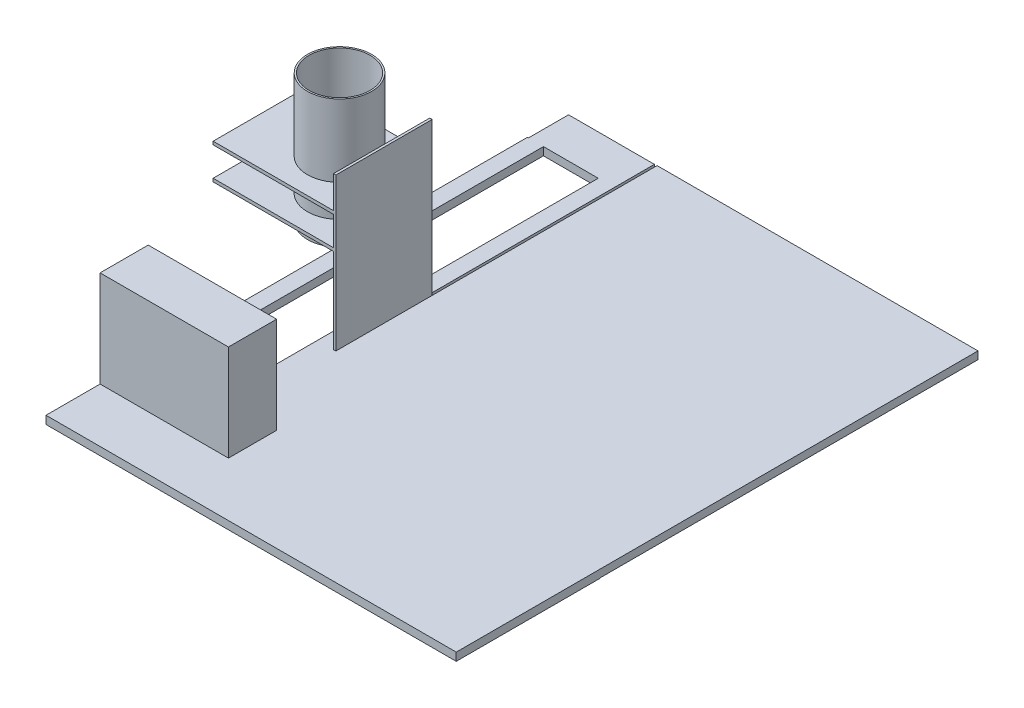
SolidWorks part; units mm, degrees
ref_plane "Front Plane" through (0, 0, 0) normal (0, 0, 1) x (1, 0, 0)
ref_plane "Top Plane" through (0, 0, 0) normal (0, 1, 0) x (1, 0, 0)
ref_plane "Right Plane" through (0, 0, 0) normal (1, 0, 0) x (0, 0, -1)
sketch "Sketch1" plane through (0, 0, 0) normal (0, 1, 0) x (1, 0, 0)
  line L1 (-61.8196, -100.3287) -> (-41.8196, -100.3287)
  line L2 (-61.8196, -100.3287) -> (-61.8196, 249.6713)
  line L3 (-61.8196, 249.6713) -> (-41.8196, 249.6713)
  line L4 (-41.8196, -100.3287) -> (-41.8196, 249.6713)
  line L5 (46.5104, -100.3287) -> (26.5104, -100.3287)
  line L6 (46.5104, -100.3287) -> (46.5104, 249.6713)
  line L7 (46.5104, 249.6713) -> (26.5104, 249.6713)
  line L8 (26.5104, -100.3287) -> (26.5104, 249.6713)
  dimension "D1" = 20
  dimension "D2" = 20
  dimension "D3" = 350
  dimension "D4" = 350
  dimension "D5" = 68.33
extrude "Boss-Extrude1" add sketch "Sketch1" along normal blind 10
sketch "Sketch2" plane through (0, 0, 0) normal (0, -1, 0) x (-1, 0, 0)
  line L1 (-46.5104, 249.6713) -> (60.5056, 249.6713)
  line L2 (-46.5104, 249.6713) -> (-46.5104, 299.6713)
  line L3 (-46.5104, 299.6713) -> (60.5056, 299.6713)
  line L4 (60.5056, 249.6713) -> (60.5056, 299.6713)
  dimension "D1" = 50
extrude "Boss-Extrude2" add sketch "Sketch2" along normal blind 0.001 and the other way blind 10
sketch "Sketch3" plane through (46.5104, 0, 0) normal (1, 0, 0) x (0, 0, -1)
  line L1 (-100.3287, 0) -> (19.6713, 0)
  line L2 (-100.3287, 0) -> (-100.3287, 200)
  line L3 (-100.3287, 200) -> (19.6713, 200)
  line L4 (19.6713, 0) -> (19.6713, 200)
  dimension "D1" = 120
  dimension "D2" = 200
extrude "Boss-Extrude3" add sketch "Sketch3" along normal blind 3
sketch "Sketch4" plane through (46.5104, 0, 0) normal (-1, 0, 0) x (0, 0, 1)
  line L0 (-19.6713, 10) -> (-19.6713, 200) construction
  line L1 (-19.6713, 160) -> (100.3287, 160)
  line L2 (-19.6713, 160) -> (-19.6713, 156)
  line L3 (-19.6713, 156) -> (100.3287, 156)
  line L4 (100.3287, 160) -> (100.3287, 156)
  line L5 (100.3287, 200) -> (100.3287, 10) construction
  line L6 (-19.6713, 200) -> (100.3287, 200) construction
  line L7 (100.3287, 120) -> (-19.6713, 120)
  line L8 (100.3287, 120) -> (100.3287, 116)
  line L9 (100.3287, 116) -> (-19.6713, 116)
  line L10 (-19.6713, 120) -> (-19.6713, 116)
  dimension "D1" = 40
  dimension "D2" = 80
  dimension "D3" = 4
  dimension "D4" = 4
extrude "Boss-Extrude4" add sketch "Sketch4" along normal blind 150 contours L7 L10 L9 L8 | L3 L4 L1 L2
sketch "Sketch5" plane through (0, 160, 0) normal (0, 1, 0) x (1, 0, 0)
  line L0 (46.5104, 19.6713) -> (46.5104, -100.3287) construction
  circle A0 centre (-8.4896, -37.7813) radius 40
  dimension "D1" = 55
extrude "Cut-Extrude1" cut sketch "Sketch5" against normal blind 90
sketch "Sketch6" plane through (0, 160, 0) normal (0, 1, 0) x (1, 0, 0)
  circle A0 centre (-8.4896, -37.7813) radius 40
extrude "Boss-Extrude5" add sketch "Sketch6" along normal blind 90 and the other way blind 70
sketch "Sketch7" plane through (0, 250, 0) normal (0, 1, 0) x (1, 0, 0)
  circle A0 centre (-8.4896, -37.7813) radius 38
extrude "Cut-Extrude2" cut sketch "Sketch7" against normal blind 176
sketch "Sketch8" plane through (0, 0, 100.3287) normal (0, 0, 1) x (1, 0, 0)
  line L0 (-61.8196, 0) -> (-41.8196, 0) construction
  line L1 (-61.8196, 10) -> (-41.8196, 10)
  line L2 (-61.8196, 10) -> (-61.8196, 0)
  line L3 (-61.8196, 0) -> (-41.8196, 0)
  line L4 (-41.8196, 10) -> (-41.8196, 0)
  line L5 (26.5104, 0) -> (49.5104, 0) construction
  line L6 (26.5104, 10) -> (49.5104, 10)
  line L7 (26.5104, 10) -> (26.5104, 0)
  line L8 (26.5104, 0) -> (49.5104, 0)
  line L9 (49.5104, 10) -> (49.5104, 0)
  line L10 (49.5104, 200) -> (49.5104, 0) construction
extrude "Boss-Extrude6" add sketch "Sketch8" along normal blind 70
sketch "Sketch9" plane through (49.5104, 0, 0) normal (1, 0, 0) x (0, 0, -1)
  line L1 (-170.3287, 10) -> (299.9956, 10)
  line L2 (-170.3287, 10) -> (-170.3287, 0.4612)
  line L3 (-170.3287, 0.4612) -> (299.9956, 0.4612)
  line L4 (299.9956, 10) -> (299.9956, 0.4612)
extrude "Boss-Extrude7" add sketch "Sketch9" along normal blind 400
sketch "Sketch10" plane through (0, 0, 170.3287) normal (0, 0, 1) x (1, 0, 0)
  line L1 (449.5104, 10) -> (-61.8196, 10)
  line L2 (449.5104, 10) -> (449.5104, 0)
  line L3 (449.5104, 0) -> (-61.8196, 0)
  line L4 (-61.8196, 10) -> (-61.8196, 0)
extrude "Boss-Extrude8" add sketch "Sketch10" along normal blind 180
sketch "Sketch11" plane through (0, 10, 0) normal (0, 1, 0) x (1, 0, 0)
  line L0 (-61.8196, 249.6713) -> (-61.8196, -350.3287) construction
  line L1 (-61.8196, -222.9219) -> (98.1804, -222.9219)
  line L2 (-61.8196, -222.9219) -> (-61.8196, -282.9219)
  line L3 (-61.8196, -282.9219) -> (98.1804, -282.9219)
  line L4 (98.1804, -222.9219) -> (98.1804, -282.9219)
  dimension "D1" = 60
  dimension "D2" = 160
extrude "Boss-Extrude9" add sketch "Sketch11" along normal blind 120
